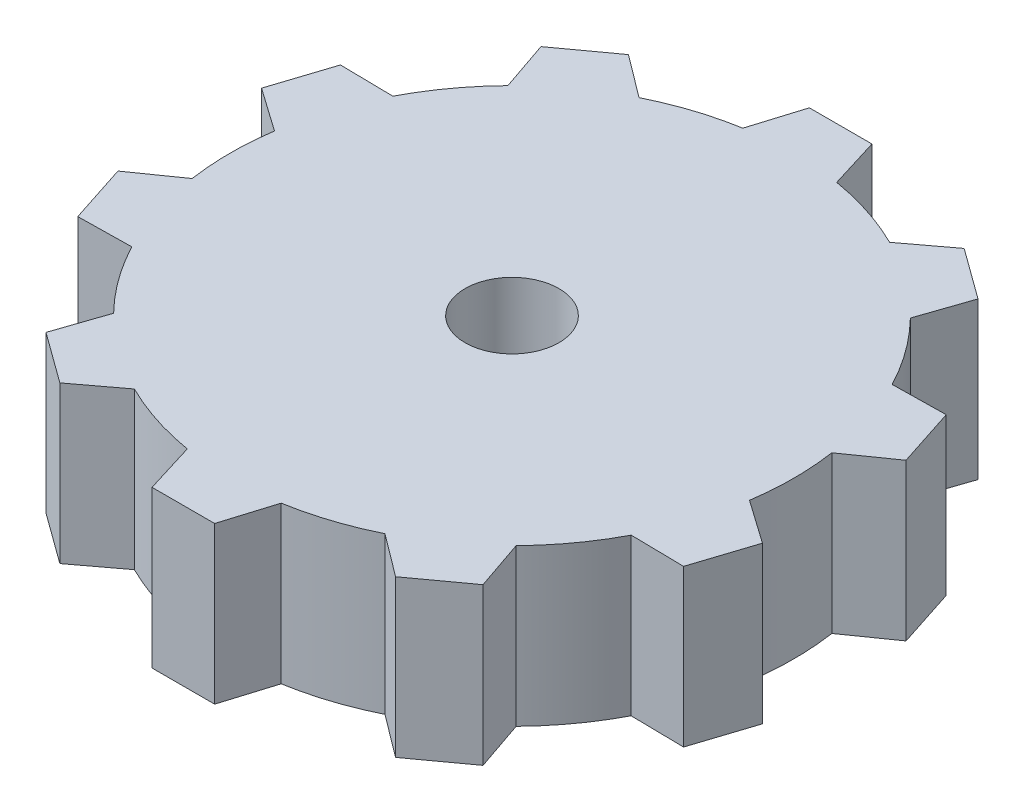
SolidWorks part; units mm, degrees
ref_plane "前视基准面" through (0, 0, 0) normal (0, 0, 1) x (1, 0, 0)
ref_plane "上视基准面" through (0, 0, 0) normal (0, 1, 0) x (1, 0, 0)
ref_plane "右视基准面" through (0, 0, 0) normal (1, 0, 0) x (0, 0, -1)
sketch "草图1" plane through (0, 0, 0) normal (0, 1, 0) x (1, 0, 0)
  circle A0 centre (0, 0) radius 9
  circle A1 centre (0, 0) radius 1.5
  dimension "D1" = 3
  dimension "D3" = 18
extrude "凸台-拉伸1" add sketch "草图1" along normal blind 5 contours A0 A1
sketch "草图2" plane through (0, 5, 0) normal (0, 1, 0) x (1, 0, 0)
  line L0 (0, 0) -> (0, 9) construction
  line L1 (0, 9) -> (0, 6.2976) construction
  line L2 (1, 10.5) -> (-1, 10.5)
  line L3 (-1, 10.5) -> (-1.5, 8.8741)
  line L4 (1, 10.5) -> (1.5, 8.8741)
  circle A0 centre (0, 0) radius 9 construction
  circle A2 centre (0, 0) radius 9
  circle A3 centre (0, 0) radius 9
  point P12 (0, 10.5)
  circle M7 centre (0, 0) radius 9
  dimension "D2" = 1
  dimension "D3" = 1.5
  dimension "D4" = 1.5
  dimension "D1" = 0
extrude "凸台-拉伸2" add sketch "草图2" against normal up to surface (5 mm away) contours L4 L2 L3 M7 up to face at (0, 0, 1.5)
pattern_circular "阵列(圆周)1" count 10 over 360 about axis through (0, 0, 0) along (0, 1, 0) of "凸台-拉伸2"
